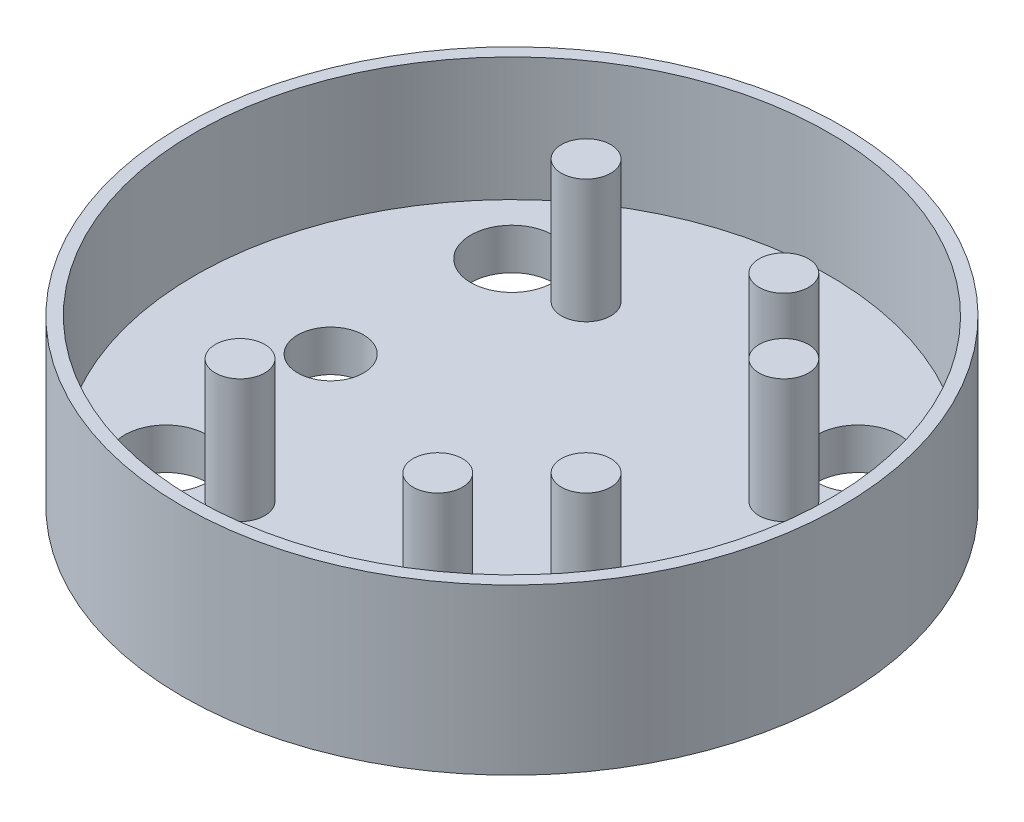
SolidWorks part; units mm, degrees
ref_plane "Front Plane" through (0, 0, 0) normal (0, 0, 1) x (1, 0, 0)
ref_plane "Top Plane" through (0, 0, 0) normal (0, 1, 0) x (1, 0, 0)
ref_plane "Right Plane" through (0, 0, 0) normal (1, 0, 0) x (0, 0, -1)
sketch "Sketch1" plane through (0, 0, 0) normal (0, 1, 0) x (1, 0, 0)
  circle A0 centre (0, 0) radius 40
  circle A1 centre (-21, 21) radius 5
  circle A2 centre (-21, -21) radius 5
  circle A3 centre (21, -21) radius 5
  circle A4 centre (21, 21) radius 5
extrude "Boss-Extrude1" add sketch "Sketch1" along normal blind 5
sketch "Sketch2" plane through (0, 5, 0) normal (0, 1, 0) x (1, 0, 0)
  circle A0 centre (0, 0) radius 38.5
  circle A1 centre (-12, 21) radius 3
  circle A2 centre (12, 21) radius 3
  circle A3 centre (21, 12) radius 3
  circle A4 centre (21, -12) radius 3
  circle A5 centre (12, -21) radius 3
  circle A6 centre (-12, -21) radius 3
  circle M4 centre (0, 0) radius 40
extrude "Boss-Extrude2" add sketch "Sketch2" along normal blind 15 contours A0 M4 | A6 | A5 | A4 | A3 | A2 | A1
sketch "Sketch5" plane through (0, 0, 0) normal (0, -1, 0) x (1, 0, 0)
  line L0 (0, 0) -> (-22, 0)
  circle A0 centre (-22, 0) radius 4
  dimension "D1" = 8
extrude "Cut-Extrude1" cut sketch "Sketch5" against normal blind 5 contours A0
